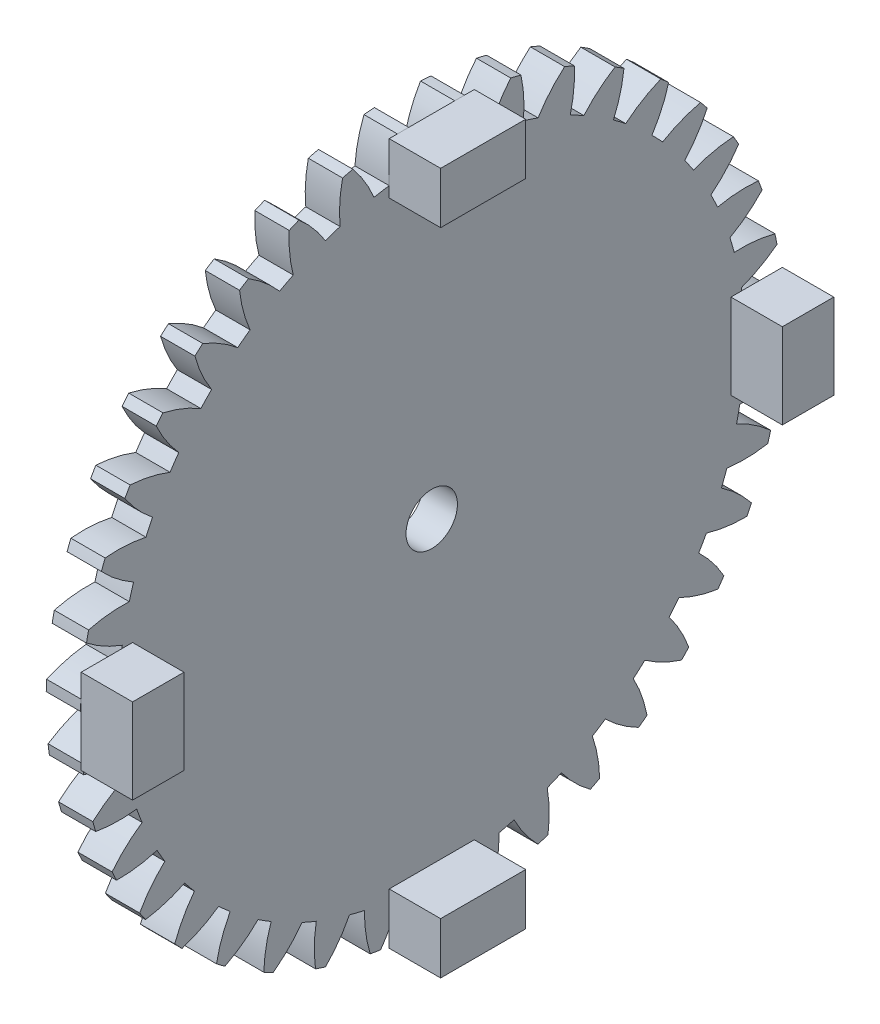
SolidWorks part; units mm, degrees
ref_plane "Plane1" through (0, 0, 0) normal (0, 0, 1) x (1, 0, 0)
ref_plane "Plane2" through (0, 0, 0) normal (0, 1, 0) x (1, 0, 0)
ref_plane "Plane3" through (0, 0, 0) normal (1, 0, 0) x (0, 0, -1)
sketch "HoldingSke" plane through (0, 0, 0) normal (0, 1, 0) x (1, 0, 0)
  line L0 (0, 0) -> (0.7771, -0.6293)
  line L1 (-15, 0) -> (100, 0) construction
  line L2 (0, 0) -> (-2.1039, 2.3779)
  line L3 (0, 0) -> (-11.863, 4.5341)
  line L4 (0, 0) -> (6.7114, 5.4348)
  line L5 (0, 0) -> (-46.8476, -17.4728)
  line L6 (0, 0) -> (-1.6579, -1.1186)
  line L7 (-2.1039, 2.3779) -> (8.6586, 51.2059)
  line L8 (-76.2, 54.61) -> (-75.7, 54.61)
  line L9 (-71.009, 38.7566) -> (-53.1078, 45.2721)
  line L10 (-76.2, 71.12) -> (104.1128, 71.12)
  line L11 (0, 0) -> (-2, 0)
  line L12 (-76.2, 101.6) -> (-76.162, 101.6)
  line L13 (24.9733, 27.94) -> (52.9518, 28.4284)
  line L14 (24.9733, 27.94) -> (24.9743, 27.94)
  line L15 (24.9733, 27.94) -> (100.4006, 29.5858)
  line L16 (-63.627, -1) -> (-12.827, -1)
  circle A0 centre (0, 0) radius 1.5
  circle A1 centre (0, 0) radius 18.249
  circle A2 centre (0, 0) radius 37.5
  circle A3 centre (0, 0) radius 1.5
  dimension "MHD" = 36.498
  dimension "Hub_dia" = 75
  dimension "Bore" = 3
  dimension "MBD" = 3
  dimension "Num_teeth" = 39
  dimension "Pitch" = 1
  dimension "Overall_len" = 50
  dimension "Show_teeth" = 39
  dimension "Thickness" = 2
  dimension "OAL" = 50.0001
  dimension "T_dim" = 0.5
  dimension "Ap" = 20
  dimension "H" = 19.05
  dimension "Pitch_radius" = 180.3128
  dimension "Width" = 2
  dimension "Backlash" = 0.038
  dimension "Addendum_fac" = 1
  dimension "Dedendum_fac" = 1.25
  dimension "Clearance_fac" = 0.25
  dimension "Dedendum_add" = 0.001
  dimension "Module" = 1
sketch "BasProSke" plane through (0, 0, 0) normal (0, 1, 0) x (1, 0, 0)
  line L0 (-10, 0) -> (60, 0) construction
  line L1 (0, 0) -> (0, 20.5)
  line L2 (0, 0) -> (2, 0)
  line L3 (2, 0) -> (2, 20.5)
  line L4 (2, 20.5) -> (0, 20.5)
  dimension "Thickness" = 2
  dimension "Diameter" = 41
revolve "Base-Revolve" add sketch "BasProSke" angle 360 about L0
sketch "TooCutSke" plane through (0, 0, 0) normal (1, 0, 0) x (0, 0, -1)
  line L1 (0, 0) -> (0, 107) construction
  line L2 (0, 0) -> (-0.8517, 19.4814) construction
  line L3 (0, 0) -> (-3.1361, 38.8471) construction
  line L4 (-0.8517, 19.4814) -> (-1.568, 19.4236) construction
  arc A0 (0.4501, 18.2434) -> (-0.4501, 18.2434) centre (0, 0) ccw
  arc A1 (1.358, 20.4804) -> (-1.358, 20.4804) centre (0, 0) ccw
  circle A2 centre (0, 0) radius 19.5 construction
  circle A3 centre (0, 0) radius 18.324 construction
  arc A4 (-0.4501, 18.2434) -> (-1.358, 20.4804) centre (-8.0443, 16.4638) ccw
  arc A5 (1.358, 20.4804) -> (0.4501, 18.2434) centre (8.0443, 16.4638) ccw
  dimension "Root_dia" = 36.498
  dimension "Overcut_dia" = 41.0508
  dimension "Pitch_dia" = 39
  dimension "Base_dia" = 36.648
  dimension "Flank_rad" = 7.8
  dimension "Half_ang" = 4.615
  dimension "Half_CT" = 0.7187
extrude "ToothCut" cut sketch "TooCutSke" along normal through all
fillet "Breaks" [suppressed] radius 0.02
fillet "RootFillets" [suppressed] radius 0.251
pattern_circular "TeethCuts" count 39 every 9.231 about axis through (-10, 0, 0) along (1, 0, 0) of "ToothCut", "RootFillets", "Breaks"
sketch "HubNeaOneSke" plane through (0, 0, 0) normal (-1, 0, 0) x (0, 0, 1)
  circle A0 centre (0, 0) radius 18.249
  dimension "Diameter" = 36.498
extrude "HubNearOne" [suppressed] add sketch "HubNeaOneSke" along normal blind 48.0001
sketch "HubNeaBotSke" plane through (0, 0, 0) normal (-1, 0, 0) x (0, 0, 1)
  circle A0 centre (0, 0) radius 18.249
  dimension "Diameter" = 36.498
extrude "HubNearBoth" [suppressed] add sketch "HubNeaBotSke" along normal blind 24
ref_plane "FarPln" through (2, 0, 0) normal (1, 0, 0) x (0, 0, -1)
sketch "HubFarSke" plane through (2, 0, 0) normal (1, 0, 0) x (0, 0, -1)
  circle A0 centre (0, 0) radius 18.249
  dimension "Diameter" = 36.498
extrude "HubFar" [suppressed] add sketch "HubFarSke" along normal blind 24
sketch "BorSke" plane through (0, 0, 0) normal (1, 0, 0) x (0, 0, -1)
  circle A0 centre (0, 0) radius 1.5
  dimension "Diameter" = 3
extrude "Bore" cut sketch "BorSke" along normal mid plane 100.0001
sketch "KeySke" plane through (0, 0, 0) normal (1, 0, 0) x (0, 0, -1)
  line L0 (-0.6, 0) -> (-0.6, 2)
  line L1 (-0.6, 2) -> (0.6, 2)
  line L2 (0.6, 2) -> (0.6, 0)
  line L3 (0, 0) -> (0, 34) construction
  line L4 (-0.6, 0) -> (0.6, 0)
  dimension "Offset" = 2
  dimension "Width" = 1.2
extrude "Keyway" [suppressed] cut sketch "KeySke" along normal mid plane 100.0001
pattern_circular "Keyway2" [suppressed] count 2 every 90 about axis through (-10, 0, 0) along (1, 0, 0)
sketch "Croquis1" plane through (2, 0, 0) normal (1, 0, 0) x (0, 0, -1)
  line L0 (0, 0) -> (0, 18.249) construction
  line L6 (17.4559, -2.4822) -> (20.4559, -2.4822)
  line L22 (2.4822, 17.4559) -> (-2.4822, 17.4559)
  line L23 (2.4822, 17.4559) -> (2.4822, 20.4559)
  line L24 (2.4822, 20.4559) -> (-2.4822, 20.4559)
  line L25 (-2.4822, 17.4559) -> (-2.4822, 20.4559)
  line L26 (2.4822, 17.4559) -> (-2.4822, 20.4559) construction
  line L27 (2.4822, 20.4559) -> (-2.4822, 17.4559) construction
  line L28 (17.4559, -2.4822) -> (17.4559, 2.4822)
  line L29 (17.4559, 2.4822) -> (20.4559, 2.4822)
  line L30 (20.4559, -2.4822) -> (20.4559, 2.4822)
  line L31 (-2.4822, -17.4559) -> (-2.4822, -20.4559)
  line L32 (-2.4822, -17.4559) -> (2.4822, -17.4559)
  line L33 (2.4822, -17.4559) -> (2.4822, -20.4559)
  line L34 (-2.4822, -20.4559) -> (2.4822, -20.4559)
  line L35 (-17.4559, 2.4822) -> (-20.4559, 2.4822)
  line L36 (-17.4559, 2.4822) -> (-17.4559, -2.4822)
  line L37 (-17.4559, -2.4822) -> (-20.4559, -2.4822)
  line L38 (-20.4559, 2.4822) -> (-20.4559, -2.4822)
  arc A156 (-20.4934, 0.5186) -> (-18.2468, -0.2849) centre (-16.7744, 7.3749) ccw
  arc A157 (-18.2468, -0.2849) -> (-18.2105, -1.1843) centre (0, 0) ccw
  arc A158 (-18.2105, -1.1843) -> (-20.3853, -2.1659) centre (-16.1266, -8.7007) ccw
  arc A159 (-20.3853, -2.1659) -> (-20.3112, -2.7755) centre (0, 0) ccw
  arc A160 (-20.3112, -2.7755) -> (-17.9648, -3.2082) centre (-17.7402, 4.5886) ccw
  arc A161 (-17.9648, -3.2082) -> (-17.7847, -4.0901) centre (0, 0) ccw
  arc A162 (-17.7847, -4.0901) -> (-19.7738, -5.4079) centre (-14.522, -11.175) ccw
  arc A163 (-19.7738, -5.4079) -> (-19.603, -5.9977) centre (0, 0) ccw
  arc A164 (-19.603, -5.9977) -> (-17.2175, -6.0484) centre (-18.2465, 1.6834) ccw
  arc A165 (-17.2175, -6.0484) -> (-16.8983, -6.89) centre (0, 0) ccw
  arc A166 (-16.8983, -6.89) -> (-18.6503, -8.5098) centre (-12.5414, -13.3597) ccw
  arc A167 (-18.6503, -8.5098) -> (-18.387, -9.0646) centre (0, 0) ccw
  arc A168 (-18.387, -9.0646) -> (-16.0243, -8.732) centre (-18.2803, -1.2653) ccw
  arc A169 (-16.0243, -8.732) -> (-15.5743, -9.5115) centre (0, 0) ccw
  arc A170 (-15.5743, -9.5115) -> (-17.0437, -11.3914) centre (-10.2359, -15.1985) ccw
  arc A171 (-17.0437, -11.3914) -> (-16.6949, -11.8967) centre (0, 0) ccw
  arc A172 (-16.6949, -11.8967) -> (-14.4161, -11.1894) centre (-17.8406, -4.1813) ccw
  arc A173 (-14.4161, -11.1894) -> (-13.8468, -11.8866) centre (0, 0) ccw
  arc A174 (-13.8468, -11.8866) -> (-14.9957, -13.9778) centre (-7.6654, -16.6437) ccw
  arc A175 (-14.9957, -13.9778) -> (-14.5703, -14.4207) centre (0, 0) ccw
  arc A176 (-14.5703, -14.4207) -> (-12.4345, -13.357) centre (-16.9388, -6.989) ccw
  arc A177 (-12.4345, -13.357) -> (-11.7608, -13.9539) centre (0, 0) ccw
  arc A178 (-11.7608, -13.9539) -> (-12.5593, -16.2023) centre (-4.8963, -17.6577) ccw
  arc A179 (-12.5593, -16.2023) -> (-12.0684, -16.5712) centre (0, 0) ccw
  arc A180 (-12.0684, -16.5712) -> (-10.1309, -15.1786) centre (-15.5984, -9.6156) ccw
  arc A181 (-10.1309, -15.1786) -> (-9.3701, -15.6597) centre (0, 0) ccw
  arc A182 (-9.3701, -15.6597) -> (-9.7976, -18.0071) centre (-2.0004, -18.2145) ccw
  arc A183 (-9.7976, -18.0071) -> (-9.2539, -18.2925) centre (0, 0) ccw
  arc A184 (-9.2539, -18.2925) -> (-7.5649, -16.6072) centre (-13.8539, -11.9933) ccw
  arc A185 (-7.5649, -16.6072) -> (-6.7368, -16.96) centre (0, 0) ccw
  arc A186 (-6.7368, -16.96) -> (-6.7822, -19.3456) centre (0.9474, -18.2995) ccw
  arc A187 (-6.7822, -19.3456) -> (-6.1997, -19.54) centre (0, 0) ccw
  arc A188 (-6.1997, -19.54) -> (-4.8029, -17.6056) centre (-11.7506, -14.0603) ccw
  arc A189 (-4.8029, -17.6056) -> (-3.929, -17.821) centre (0, 0) ccw
  arc A190 (-3.929, -17.821) -> (-3.5911, -20.183) centre (3.8705, -17.9106) ccw
  arc A191 (-3.5911, -20.183) -> (-2.985, -20.2815) centre (0, 0) ccw
  arc A192 (-2.985, -20.2815) -> (-1.9166, -18.1481) centre (-9.343, -15.7631) ccw
  arc A193 (-1.9166, -18.1481) -> (-1.0194, -18.2205) centre (0, 0) ccw
  arc A194 (-1.0194, -18.2205) -> (-0.307, -20.4977) centre (6.6935, -17.0577) ccw
  arc A195 (-0.307, -20.4977) -> (0.307, -20.4977) centre (0, 0) ccw
  arc A196 (0.307, -20.4977) -> (1.0194, -18.2205) centre (-6.6935, -17.0577) ccw
  arc A197 (1.0194, -18.2205) -> (1.9166, -18.1481) centre (0, 0) ccw
  arc A198 (1.9166, -18.1481) -> (2.985, -20.2815) centre (9.343, -15.7631) ccw
  arc A199 (2.985, -20.2815) -> (3.5911, -20.183) centre (0, 0) ccw
  arc A200 (3.5911, -20.183) -> (3.929, -17.821) centre (-3.8705, -17.9106) ccw
  arc A201 (3.929, -17.821) -> (4.8029, -17.6056) centre (0, 0) ccw
  arc A202 (4.8029, -17.6056) -> (6.1997, -19.54) centre (11.7506, -14.0603) ccw
  arc A203 (6.1997, -19.54) -> (6.7822, -19.3456) centre (0, 0) ccw
  arc A204 (6.7822, -19.3456) -> (6.7368, -16.96) centre (-0.9474, -18.2995) ccw
  arc A205 (6.7368, -16.96) -> (7.5649, -16.6072) centre (0, 0) ccw
  arc A206 (7.5649, -16.6072) -> (9.2539, -18.2925) centre (13.8539, -11.9933) ccw
  arc A207 (9.2539, -18.2925) -> (9.7976, -18.0071) centre (0, 0) ccw
  arc A208 (9.7976, -18.0071) -> (9.3701, -15.6597) centre (2.0004, -18.2145) ccw
  arc A209 (9.3701, -15.6597) -> (10.1309, -15.1786) centre (0, 0) ccw
  arc A210 (10.1309, -15.1786) -> (12.0684, -16.5712) centre (15.5984, -9.6156) ccw
  arc A211 (12.0684, -16.5712) -> (12.5593, -16.2023) centre (0, 0) ccw
  arc A212 (12.5593, -16.2023) -> (11.7608, -13.9539) centre (4.8963, -17.6577) ccw
  arc A213 (11.7608, -13.9539) -> (12.4345, -13.357) centre (0, 0) ccw
  arc A214 (12.4345, -13.357) -> (14.5703, -14.4207) centre (16.9388, -6.989) ccw
  arc A215 (14.5703, -14.4207) -> (14.9957, -13.9778) centre (0, 0) ccw
  arc A216 (14.9957, -13.9778) -> (13.8468, -11.8866) centre (7.6654, -16.6437) ccw
  arc A217 (13.8468, -11.8866) -> (14.4161, -11.1894) centre (0, 0) ccw
  arc A218 (14.4161, -11.1894) -> (16.6949, -11.8967) centre (17.8406, -4.1813) ccw
  arc A219 (16.6949, -11.8967) -> (17.0437, -11.3914) centre (0, 0) ccw
  arc A220 (17.0437, -11.3914) -> (15.5743, -9.5115) centre (10.2359, -15.1985) ccw
  arc A221 (15.5743, -9.5115) -> (16.0243, -8.732) centre (0, 0) ccw
  arc A222 (16.0243, -8.732) -> (18.387, -9.0646) centre (18.2803, -1.2653) ccw
  arc A223 (18.387, -9.0646) -> (18.6503, -8.5098) centre (0, 0) ccw
  arc A224 (18.6503, -8.5098) -> (16.8983, -6.89) centre (12.5414, -13.3597) ccw
  arc A225 (16.8983, -6.89) -> (17.2175, -6.0484) centre (0, 0) ccw
  arc A226 (17.2175, -6.0484) -> (19.603, -5.9977) centre (18.2465, 1.6834) ccw
  arc A227 (19.603, -5.9977) -> (19.7738, -5.4079) centre (0, 0) ccw
  arc A228 (19.7738, -5.4079) -> (17.7847, -4.0901) centre (14.522, -11.175) ccw
  arc A229 (17.7847, -4.0901) -> (17.9648, -3.2082) centre (0, 0) ccw
  arc A230 (17.9648, -3.2082) -> (20.3112, -2.7755) centre (17.7402, 4.5886) ccw
  arc A231 (20.3112, -2.7755) -> (20.3853, -2.1659) centre (0, 0) ccw
  arc A232 (20.3853, -2.1659) -> (18.2105, -1.1843) centre (16.1266, -8.7007) ccw
  arc A233 (18.2105, -1.1843) -> (18.2468, -0.2849) centre (0, 0) ccw
  arc A234 (18.2468, -0.2849) -> (20.4934, 0.5186) centre (16.7744, 7.3749) ccw
  arc A235 (20.4934, 0.5186) -> (20.4687, 1.1321) centre (0, 0) ccw
  arc A236 (20.4687, 1.1321) -> (18.1647, 1.7522) centre (17.3134, -6.0012) ccw
  arc A237 (18.1647, 1.7522) -> (18.0562, 2.6458) centre (0, 0) ccw
  arc A238 (18.0562, 2.6458) -> (20.1449, 3.7993) centre (15.3742, 9.9702) ccw
  arc A239 (20.1449, 3.7993) -> (20.022, 4.4009) centre (0, 0) ccw
  arc A240 (20.022, 4.4009) -> (17.6484, 4.6434) centre (18.0519, -3.1462) ccw
  arc A241 (17.6484, 4.6434) -> (17.3979, 5.5079) centre (0, 0) ccw
  arc A242 (17.3979, 5.5079) -> (19.2746, 6.9815) centre (13.5757, 12.3073) ccw
  arc A243 (19.2746, 6.9815) -> (19.0568, 7.5557) centre (0, 0) ccw
  arc A244 (19.0568, 7.5557) -> (16.675, 7.4142) centre (18.3228, -0.2097) ccw
  arc A245 (16.675, 7.4142) -> (16.2891, 8.2274) centre (0, 0) ccw
  arc A246 (16.2891, 8.2274) -> (17.905, 9.983) centre (11.4257, 14.3256) ccw
  arc A247 (17.905, 9.983) -> (17.598, 10.5147) centre (0, 0) ccw
  arc A248 (17.598, 10.5147) -> (15.2697, 9.9931) centre (18.1192, 2.7322) ccw
  arc A249 (15.2697, 9.9931) -> (14.7584, 10.7339) centre (0, 0) ccw
  arc A250 (14.7584, 10.7339) -> (16.0718, 12.7259) centre (8.9798, 15.9729) ccw
  arc A251 (16.0718, 12.7259) -> (15.6834, 13.2015) centre (0, 0) ccw
  arc A252 (15.6834, 13.2015) -> (13.469, 12.3131) centre (17.4463, 5.6033) ccw
  arc A253 (13.469, 12.3131) -> (12.8455, 12.9623) centre (0, 0) ccw
  arc A254 (12.8455, 12.9623) -> (13.8223, 15.1392) centre (6.3013, 17.2065) ccw
  arc A255 (13.8223, 15.1392) -> (13.3627, 15.5463) centre (0, 0) ccw
  arc A256 (13.3627, 15.5463) -> (11.3194, 14.3142) centre (16.3215, 8.3293) ccw
  arc A257 (11.3194, 14.3142) -> (10.5998, 14.855) centre (0, 0) ccw
  arc A258 (10.5998, 14.855) -> (11.2148, 17.1604) centre (3.4595, 17.9945) ccw
  arc A259 (11.2148, 17.1604) -> (10.6958, 17.4885) centre (0, 0) ccw
  arc A260 (10.6958, 17.4885) -> (8.8767, 15.9446) centre (14.774, 10.8396) ccw
  arc A261 (8.8767, 15.9446) -> (8.0796, 16.3629) centre (0, 0) ccw
  arc A262 (8.0796, 16.3629) -> (8.3169, 18.7371) centre (0.5282, 18.3164) ccw
  arc A263 (8.3169, 18.7371) -> (7.752, 18.9778) centre (0, 0) ccw
  arc A264 (7.752, 18.9778) -> (6.204, 17.1621) centre (12.8439, 13.0692) ccw
  arc A265 (6.204, 17.1621) -> (5.3502, 17.4471) centre (0, 0) ccw
  arc A266 (5.3502, 17.4471) -> (5.2035, 19.8286) centre (-2.4168, 18.1639) ccw
  arc A267 (5.2035, 19.8286) -> (4.6073, 19.9755) centre (0, 0) ccw
  arc A268 (4.6073, 19.9755) -> (3.3707, 17.935) centre (10.5811, 14.9602) ccw
  arc A269 (3.3707, 17.935) -> (2.4822, 18.0794) centre (0, 0) ccw
  arc A270 (2.4822, 18.0794) -> (1.9554, 20.4065) centre (-5.2992, 17.541) ccw
  arc A271 (1.9554, 20.4065) -> (1.3434, 20.4559) centre (0, 0) ccw
  arc A272 (1.3434, 20.4559) -> (0.4501, 18.2434) centre (8.0443, 16.4638) ccw
  arc A273 (0.4501, 18.2434) -> (-0.4501, 18.2434) centre (0, 0) ccw
  arc A274 (-0.4501, 18.2434) -> (-1.3434, 20.4559) centre (-8.0443, 16.4638) ccw
  arc A275 (-1.3434, 20.4559) -> (-1.9554, 20.4065) centre (0, 0) ccw
  arc A276 (-1.9554, 20.4065) -> (-2.4822, 18.0794) centre (5.2992, 17.541) ccw
  arc A277 (-2.4822, 18.0794) -> (-3.3707, 17.935) centre (0, 0) ccw
  arc A278 (-3.3707, 17.935) -> (-4.6073, 19.9755) centre (-10.5811, 14.9602) ccw
  arc A279 (-4.6073, 19.9755) -> (-5.2035, 19.8286) centre (0, 0) ccw
  arc A280 (-5.2035, 19.8286) -> (-5.3502, 17.4471) centre (2.4168, 18.1639) ccw
  arc A281 (-5.3502, 17.4471) -> (-6.204, 17.1621) centre (0, 0) ccw
  arc A282 (-6.204, 17.1621) -> (-7.752, 18.9778) centre (-12.8439, 13.0692) ccw
  arc A283 (-7.752, 18.9778) -> (-8.3169, 18.7371) centre (0, 0) ccw
  arc A284 (-8.3169, 18.7371) -> (-8.0796, 16.3629) centre (-0.5282, 18.3164) ccw
  arc A285 (-8.0796, 16.3629) -> (-8.8767, 15.9446) centre (0, 0) ccw
  arc A286 (-8.8767, 15.9446) -> (-10.6958, 17.4885) centre (-14.774, 10.8396) ccw
  arc A287 (-10.6958, 17.4885) -> (-11.2148, 17.1604) centre (0, 0) ccw
  arc A288 (-11.2148, 17.1604) -> (-10.5998, 14.855) centre (-3.4595, 17.9945) ccw
  arc A289 (-10.5998, 14.855) -> (-11.3194, 14.3142) centre (0, 0) ccw
  arc A290 (-11.3194, 14.3142) -> (-13.3627, 15.5463) centre (-16.3215, 8.3293) ccw
  arc A291 (-13.3627, 15.5463) -> (-13.8223, 15.1392) centre (0, 0) ccw
  arc A292 (-13.8223, 15.1392) -> (-12.8455, 12.9623) centre (-6.3013, 17.2065) ccw
  arc A293 (-12.8455, 12.9623) -> (-13.469, 12.3131) centre (0, 0) ccw
  arc A294 (-13.469, 12.3131) -> (-15.6834, 13.2015) centre (-17.4463, 5.6033) ccw
  arc A295 (-15.6834, 13.2015) -> (-16.0718, 12.7259) centre (0, 0) ccw
  arc A296 (-16.0718, 12.7259) -> (-14.7584, 10.7339) centre (-8.9798, 15.9729) ccw
  arc A297 (-14.7584, 10.7339) -> (-15.2697, 9.9931) centre (0, 0) ccw
  arc A298 (-15.2697, 9.9931) -> (-17.598, 10.5147) centre (-18.1192, 2.7322) ccw
  arc A299 (-17.598, 10.5147) -> (-17.905, 9.983) centre (0, 0) ccw
  arc A300 (-17.905, 9.983) -> (-16.2891, 8.2274) centre (-11.4257, 14.3256) ccw
  arc A301 (-16.2891, 8.2274) -> (-16.675, 7.4142) centre (0, 0) ccw
  arc A302 (-16.675, 7.4142) -> (-19.0568, 7.5557) centre (-18.3228, -0.2097) ccw
  arc A303 (-19.0568, 7.5557) -> (-19.2746, 6.9815) centre (0, 0) ccw
  arc A304 (-19.2746, 6.9815) -> (-17.3979, 5.5079) centre (-13.5757, 12.3073) ccw
  arc A305 (-17.3979, 5.5079) -> (-17.6484, 4.6434) centre (0, 0) ccw
  arc A306 (-17.6484, 4.6434) -> (-20.022, 4.4009) centre (-18.0519, -3.1462) ccw
  arc A307 (-20.022, 4.4009) -> (-20.1449, 3.7993) centre (0, 0) ccw
  arc A308 (-20.1449, 3.7993) -> (-18.0562, 2.6458) centre (-15.3742, 9.9702) ccw
  arc A309 (-18.0562, 2.6458) -> (-18.1647, 1.7522) centre (0, 0) ccw
  arc A310 (-18.1647, 1.7522) -> (-20.4687, 1.1321) centre (-17.3134, -6.0012) ccw
  arc A311 (-20.4687, 1.1321) -> (-20.4934, 0.5186) centre (0, 0) ccw
  arc A312 (-20.4934, 0.5186) -> (-18.2468, -0.2849) centre (-16.7744, 7.3749) ccw construction
  arc A313 (-18.2468, -0.2849) -> (-18.2105, -1.1843) centre (0, 0) ccw construction
  arc A314 (-18.2105, -1.1843) -> (-20.3853, -2.1659) centre (-16.1266, -8.7007) ccw construction
  arc A315 (-20.3853, -2.1659) -> (-20.3112, -2.7755) centre (0, 0) ccw construction
  arc A316 (-20.3112, -2.7755) -> (-17.9648, -3.2082) centre (-17.7402, 4.5886) ccw construction
  arc A317 (-17.9648, -3.2082) -> (-17.7847, -4.0901) centre (0, 0) ccw construction
  arc A318 (-17.7847, -4.0901) -> (-19.7738, -5.4079) centre (-14.522, -11.175) ccw construction
  arc A319 (-19.7738, -5.4079) -> (-19.603, -5.9977) centre (0, 0) ccw construction
  arc A320 (-19.603, -5.9977) -> (-17.2175, -6.0484) centre (-18.2465, 1.6834) ccw construction
  arc A321 (-17.2175, -6.0484) -> (-16.8983, -6.89) centre (0, 0) ccw construction
  arc A322 (-16.8983, -6.89) -> (-18.6503, -8.5098) centre (-12.5414, -13.3597) ccw construction
  arc A323 (-18.6503, -8.5098) -> (-18.387, -9.0646) centre (0, 0) ccw construction
  arc A324 (-18.387, -9.0646) -> (-16.0243, -8.732) centre (-18.2803, -1.2653) ccw construction
  arc A325 (-16.0243, -8.732) -> (-15.5743, -9.5115) centre (0, 0) ccw construction
  arc A326 (-15.5743, -9.5115) -> (-17.0437, -11.3914) centre (-10.2359, -15.1985) ccw construction
  arc A327 (-17.0437, -11.3914) -> (-16.6949, -11.8967) centre (0, 0) ccw construction
  arc A328 (-16.6949, -11.8967) -> (-14.4161, -11.1894) centre (-17.8406, -4.1813) ccw construction
  arc A329 (-14.4161, -11.1894) -> (-13.8468, -11.8866) centre (0, 0) ccw construction
  arc A330 (-13.8468, -11.8866) -> (-14.9957, -13.9778) centre (-7.6654, -16.6437) ccw construction
  arc A331 (-14.9957, -13.9778) -> (-14.5703, -14.4207) centre (0, 0) ccw construction
  arc A332 (-14.5703, -14.4207) -> (-12.4345, -13.357) centre (-16.9388, -6.989) ccw construction
  arc A333 (-12.4345, -13.357) -> (-11.7608, -13.9539) centre (0, 0) ccw construction
  arc A334 (-11.7608, -13.9539) -> (-12.5593, -16.2023) centre (-4.8963, -17.6577) ccw construction
  arc A335 (-12.5593, -16.2023) -> (-12.0684, -16.5712) centre (0, 0) ccw construction
  arc A336 (-12.0684, -16.5712) -> (-10.1309, -15.1786) centre (-15.5984, -9.6156) ccw construction
  arc A337 (-10.1309, -15.1786) -> (-9.3701, -15.6597) centre (0, 0) ccw construction
  arc A338 (-9.3701, -15.6597) -> (-9.7976, -18.0071) centre (-2.0004, -18.2145) ccw construction
  arc A339 (-9.7976, -18.0071) -> (-9.2539, -18.2925) centre (0, 0) ccw construction
  arc A340 (-9.2539, -18.2925) -> (-7.5649, -16.6072) centre (-13.8539, -11.9933) ccw construction
  arc A341 (-7.5649, -16.6072) -> (-6.7368, -16.96) centre (0, 0) ccw construction
  arc A342 (-6.7368, -16.96) -> (-6.7822, -19.3456) centre (0.9474, -18.2995) ccw construction
  arc A343 (-6.7822, -19.3456) -> (-6.1997, -19.54) centre (0, 0) ccw construction
  arc A344 (-6.1997, -19.54) -> (-4.8029, -17.6056) centre (-11.7506, -14.0603) ccw construction
  arc A345 (-4.8029, -17.6056) -> (-3.929, -17.821) centre (0, 0) ccw construction
  arc A346 (-3.929, -17.821) -> (-3.5911, -20.183) centre (3.8705, -17.9106) ccw construction
  arc A347 (-3.5911, -20.183) -> (-2.985, -20.2815) centre (0, 0) ccw construction
  arc A348 (-2.985, -20.2815) -> (-1.9166, -18.1481) centre (-9.343, -15.7631) ccw construction
  arc A349 (-1.9166, -18.1481) -> (-1.0194, -18.2205) centre (0, 0) ccw construction
  arc A350 (-1.0194, -18.2205) -> (-0.307, -20.4977) centre (6.6935, -17.0577) ccw construction
  arc A351 (-0.307, -20.4977) -> (0.307, -20.4977) centre (0, 0) ccw construction
  arc A352 (0.307, -20.4977) -> (1.0194, -18.2205) centre (-6.6935, -17.0577) ccw construction
  arc A353 (1.0194, -18.2205) -> (1.9166, -18.1481) centre (0, 0) ccw construction
  arc A354 (1.9166, -18.1481) -> (2.985, -20.2815) centre (9.343, -15.7631) ccw construction
  arc A355 (2.985, -20.2815) -> (3.5911, -20.183) centre (0, 0) ccw construction
  arc A356 (3.5911, -20.183) -> (3.929, -17.821) centre (-3.8705, -17.9106) ccw construction
  arc A357 (3.929, -17.821) -> (4.8029, -17.6056) centre (0, 0) ccw construction
  arc A358 (4.8029, -17.6056) -> (6.1997, -19.54) centre (11.7506, -14.0603) ccw construction
  arc A359 (6.1997, -19.54) -> (6.7822, -19.3456) centre (0, 0) ccw construction
  arc A360 (6.7822, -19.3456) -> (6.7368, -16.96) centre (-0.9474, -18.2995) ccw construction
  arc A361 (6.7368, -16.96) -> (7.5649, -16.6072) centre (0, 0) ccw construction
  arc A362 (7.5649, -16.6072) -> (9.2539, -18.2925) centre (13.8539, -11.9933) ccw construction
  arc A363 (9.2539, -18.2925) -> (9.7976, -18.0071) centre (0, 0) ccw construction
  arc A364 (9.7976, -18.0071) -> (9.3701, -15.6597) centre (2.0004, -18.2145) ccw construction
  arc A365 (9.3701, -15.6597) -> (10.1309, -15.1786) centre (0, 0) ccw construction
  arc A366 (10.1309, -15.1786) -> (12.0684, -16.5712) centre (15.5984, -9.6156) ccw construction
  arc A367 (12.0684, -16.5712) -> (12.5593, -16.2023) centre (0, 0) ccw construction
  arc A368 (12.5593, -16.2023) -> (11.7608, -13.9539) centre (4.8963, -17.6577) ccw construction
  arc A369 (11.7608, -13.9539) -> (12.4345, -13.357) centre (0, 0) ccw construction
  arc A370 (12.4345, -13.357) -> (14.5703, -14.4207) centre (16.9388, -6.989) ccw construction
  arc A371 (14.5703, -14.4207) -> (14.9957, -13.9778) centre (0, 0) ccw construction
  arc A372 (14.9957, -13.9778) -> (13.8468, -11.8866) centre (7.6654, -16.6437) ccw construction
  arc A373 (13.8468, -11.8866) -> (14.4161, -11.1894) centre (0, 0) ccw construction
  arc A374 (14.4161, -11.1894) -> (16.6949, -11.8967) centre (17.8406, -4.1813) ccw construction
  arc A375 (16.6949, -11.8967) -> (17.0437, -11.3914) centre (0, 0) ccw construction
  arc A376 (17.0437, -11.3914) -> (15.5743, -9.5115) centre (10.2359, -15.1985) ccw construction
  arc A377 (15.5743, -9.5115) -> (16.0243, -8.732) centre (0, 0) ccw construction
  arc A378 (16.0243, -8.732) -> (18.387, -9.0646) centre (18.2803, -1.2653) ccw construction
  arc A379 (18.387, -9.0646) -> (18.6503, -8.5098) centre (0, 0) ccw construction
  arc A380 (18.6503, -8.5098) -> (16.8983, -6.89) centre (12.5414, -13.3597) ccw construction
  arc A381 (16.8983, -6.89) -> (17.2175, -6.0484) centre (0, 0) ccw construction
  arc A382 (17.2175, -6.0484) -> (19.603, -5.9977) centre (18.2465, 1.6834) ccw construction
  arc A383 (19.603, -5.9977) -> (19.7738, -5.4079) centre (0, 0) ccw construction
  arc A384 (19.7738, -5.4079) -> (17.7847, -4.0901) centre (14.522, -11.175) ccw construction
  arc A385 (17.7847, -4.0901) -> (17.9648, -3.2082) centre (0, 0) ccw construction
  arc A386 (17.9648, -3.2082) -> (20.3112, -2.7755) centre (17.7402, 4.5886) ccw construction
  arc A387 (20.3112, -2.7755) -> (20.3853, -2.1659) centre (0, 0) ccw construction
  arc A388 (20.3853, -2.1659) -> (18.2105, -1.1843) centre (16.1266, -8.7007) ccw construction
  arc A389 (18.2105, -1.1843) -> (18.2468, -0.2849) centre (0, 0) ccw construction
  arc A390 (18.2468, -0.2849) -> (20.4934, 0.5186) centre (16.7744, 7.3749) ccw construction
  arc A391 (20.4934, 0.5186) -> (20.4687, 1.1321) centre (0, 0) ccw construction
  arc A392 (20.4687, 1.1321) -> (18.1647, 1.7522) centre (17.3134, -6.0012) ccw construction
  arc A393 (18.1647, 1.7522) -> (18.0562, 2.6458) centre (0, 0) ccw construction
  arc A394 (18.0562, 2.6458) -> (20.1449, 3.7993) centre (15.3742, 9.9702) ccw construction
  arc A395 (20.1449, 3.7993) -> (20.022, 4.4009) centre (0, 0) ccw construction
  arc A396 (20.022, 4.4009) -> (17.6484, 4.6434) centre (18.0519, -3.1462) ccw construction
  arc A397 (17.6484, 4.6434) -> (17.3979, 5.5079) centre (0, 0) ccw construction
  arc A398 (17.3979, 5.5079) -> (19.2746, 6.9815) centre (13.5757, 12.3073) ccw construction
  arc A399 (19.2746, 6.9815) -> (19.0568, 7.5557) centre (0, 0) ccw construction
  arc A400 (19.0568, 7.5557) -> (16.675, 7.4142) centre (18.3228, -0.2097) ccw construction
  arc A401 (16.675, 7.4142) -> (16.2891, 8.2274) centre (0, 0) ccw construction
  arc A402 (16.2891, 8.2274) -> (17.905, 9.983) centre (11.4257, 14.3256) ccw construction
  arc A403 (17.905, 9.983) -> (17.598, 10.5147) centre (0, 0) ccw construction
  arc A404 (17.598, 10.5147) -> (15.2697, 9.9931) centre (18.1192, 2.7322) ccw construction
  arc A405 (15.2697, 9.9931) -> (14.7584, 10.7339) centre (0, 0) ccw construction
  arc A406 (14.7584, 10.7339) -> (16.0718, 12.7259) centre (8.9798, 15.9729) ccw construction
  arc A407 (16.0718, 12.7259) -> (15.6834, 13.2015) centre (0, 0) ccw construction
  arc A408 (15.6834, 13.2015) -> (13.469, 12.3131) centre (17.4463, 5.6033) ccw construction
  arc A409 (13.469, 12.3131) -> (12.8455, 12.9623) centre (0, 0) ccw construction
  arc A410 (12.8455, 12.9623) -> (13.8223, 15.1392) centre (6.3013, 17.2065) ccw construction
  arc A411 (13.8223, 15.1392) -> (13.3627, 15.5463) centre (0, 0) ccw construction
  arc A412 (13.3627, 15.5463) -> (11.3194, 14.3142) centre (16.3215, 8.3293) ccw construction
  arc A413 (11.3194, 14.3142) -> (10.5998, 14.855) centre (0, 0) ccw construction
  arc A414 (10.5998, 14.855) -> (11.2148, 17.1604) centre (3.4595, 17.9945) ccw construction
  arc A415 (11.2148, 17.1604) -> (10.6958, 17.4885) centre (0, 0) ccw construction
  arc A416 (10.6958, 17.4885) -> (8.8767, 15.9446) centre (14.774, 10.8396) ccw construction
  arc A417 (8.8767, 15.9446) -> (8.0796, 16.3629) centre (0, 0) ccw construction
  arc A418 (8.0796, 16.3629) -> (8.3169, 18.7371) centre (0.5282, 18.3164) ccw construction
  arc A419 (8.3169, 18.7371) -> (7.752, 18.9778) centre (0, 0) ccw construction
  arc A420 (7.752, 18.9778) -> (6.204, 17.1621) centre (12.8439, 13.0692) ccw construction
  arc A421 (6.204, 17.1621) -> (5.3502, 17.4471) centre (0, 0) ccw construction
  arc A422 (5.3502, 17.4471) -> (5.2035, 19.8286) centre (-2.4168, 18.1639) ccw construction
  arc A423 (5.2035, 19.8286) -> (4.6073, 19.9755) centre (0, 0) ccw construction
  arc A424 (4.6073, 19.9755) -> (3.3707, 17.935) centre (10.5811, 14.9602) ccw construction
  arc A425 (3.3707, 17.935) -> (2.4822, 18.0794) centre (0, 0) ccw construction
  arc A426 (2.4822, 18.0794) -> (1.9554, 20.4065) centre (-5.2992, 17.541) ccw construction
  arc A427 (1.9554, 20.4065) -> (1.3434, 20.4559) centre (0, 0) ccw construction
  arc A428 (1.3434, 20.4559) -> (0.4501, 18.2434) centre (8.0443, 16.4638) ccw construction
  arc A429 (0.4501, 18.2434) -> (-0.4501, 18.2434) centre (0, 0) ccw construction
  arc A430 (-0.4501, 18.2434) -> (-1.3434, 20.4559) centre (-8.0443, 16.4638) ccw construction
  arc A431 (-1.3434, 20.4559) -> (-1.9554, 20.4065) centre (0, 0) ccw construction
  arc A432 (-1.9554, 20.4065) -> (-2.4822, 18.0794) centre (5.2992, 17.541) ccw construction
  arc A433 (-2.4822, 18.0794) -> (-3.3707, 17.935) centre (0, 0) ccw construction
  arc A434 (-3.3707, 17.935) -> (-4.6073, 19.9755) centre (-10.5811, 14.9602) ccw construction
  arc A435 (-4.6073, 19.9755) -> (-5.2035, 19.8286) centre (0, 0) ccw construction
  arc A436 (-5.2035, 19.8286) -> (-5.3502, 17.4471) centre (2.4168, 18.1639) ccw construction
  arc A437 (-5.3502, 17.4471) -> (-6.204, 17.1621) centre (0, 0) ccw construction
  arc A438 (-6.204, 17.1621) -> (-7.752, 18.9778) centre (-12.8439, 13.0692) ccw construction
  arc A439 (-7.752, 18.9778) -> (-8.3169, 18.7371) centre (0, 0) ccw construction
  arc A440 (-8.3169, 18.7371) -> (-8.0796, 16.3629) centre (-0.5282, 18.3164) ccw construction
  arc A441 (-8.0796, 16.3629) -> (-8.8767, 15.9446) centre (0, 0) ccw construction
  arc A442 (-8.8767, 15.9446) -> (-10.6958, 17.4885) centre (-14.774, 10.8396) ccw construction
  arc A443 (-10.6958, 17.4885) -> (-11.2148, 17.1604) centre (0, 0) ccw construction
  arc A444 (-11.2148, 17.1604) -> (-10.5998, 14.855) centre (-3.4595, 17.9945) ccw construction
  arc A445 (-10.5998, 14.855) -> (-11.3194, 14.3142) centre (0, 0) ccw construction
  arc A446 (-11.3194, 14.3142) -> (-13.3627, 15.5463) centre (-16.3215, 8.3293) ccw construction
  arc A447 (-13.3627, 15.5463) -> (-13.8223, 15.1392) centre (0, 0) ccw construction
  arc A448 (-13.8223, 15.1392) -> (-12.8455, 12.9623) centre (-6.3013, 17.2065) ccw construction
  arc A449 (-12.8455, 12.9623) -> (-13.469, 12.3131) centre (0, 0) ccw construction
  arc A450 (-13.469, 12.3131) -> (-15.6834, 13.2015) centre (-17.4463, 5.6033) ccw construction
  arc A451 (-15.6834, 13.2015) -> (-16.0718, 12.7259) centre (0, 0) ccw construction
  arc A452 (-16.0718, 12.7259) -> (-14.7584, 10.7339) centre (-8.9798, 15.9729) ccw construction
  arc A453 (-14.7584, 10.7339) -> (-15.2697, 9.9931) centre (0, 0) ccw construction
  arc A454 (-15.2697, 9.9931) -> (-17.598, 10.5147) centre (-18.1192, 2.7322) ccw construction
  arc A455 (-17.598, 10.5147) -> (-17.905, 9.983) centre (0, 0) ccw construction
  arc A456 (-17.905, 9.983) -> (-16.2891, 8.2274) centre (-11.4257, 14.3256) ccw construction
  arc A457 (-16.2891, 8.2274) -> (-16.675, 7.4142) centre (0, 0) ccw construction
  arc A458 (-16.675, 7.4142) -> (-19.0568, 7.5557) centre (-18.3228, -0.2097) ccw construction
  arc A459 (-19.0568, 7.5557) -> (-19.2746, 6.9815) centre (0, 0) ccw construction
  arc A460 (-19.2746, 6.9815) -> (-17.3979, 5.5079) centre (-13.5757, 12.3073) ccw construction
  arc A461 (-17.3979, 5.5079) -> (-17.6484, 4.6434) centre (0, 0) ccw construction
  arc A462 (-17.6484, 4.6434) -> (-20.022, 4.4009) centre (-18.0519, -3.1462) ccw construction
  arc A463 (-20.022, 4.4009) -> (-20.1449, 3.7993) centre (0, 0) ccw construction
  arc A464 (-20.1449, 3.7993) -> (-18.0562, 2.6458) centre (-15.3742, 9.9702) ccw construction
  arc A465 (-18.0562, 2.6458) -> (-18.1647, 1.7522) centre (0, 0) ccw construction
  arc A466 (-18.1647, 1.7522) -> (-20.4687, 1.1321) centre (-17.3134, -6.0012) ccw construction
  arc A467 (-20.4687, 1.1321) -> (-20.4934, 0.5186) centre (0, 0) ccw construction
  point P3 (0, 18.9559)
  point P11 (-20.1449, 0.5186)
  point P18 (0, 0)
  point P24 (-20.4559, -2.7755)
  point P63 (0, 0)
  dimension "D2" = 3
  dimension "D3" = 4
  dimension "D1" = 0
extrude "Saliente-Extruir1" add sketch "Croquis1" along normal blind 3
equation "' \"Module@HoldingSke\" = 6.35"
equation "' \"Num_teeth@HoldingSke\" = 12"
equation "' \"Ap@HoldingSke\" =  20"
equation "' \"Ap@HoldingSke\" = 20"
equation "' \"Width@HoldingSke\" = 0.5 * 25.4"
equation "' \"Hub_dia@HoldingSke\"= 1 * 25.4"
equation "' \"Hub_dia@HoldingSke\" = 1 * 25.4"
equation "' \"Overall_len@HoldingSke\" = 1.0 * 25.4"
equation "' \"Bore@HoldingSke\" = 0.75 * 25.4"
equation "' \"T_dim@HoldingSke\" = 0.1 * 25.4"
equation "' \"Width@KeySke\" = 0.25 * 25.4"
equation "' \"Show_teeth@HoldingSke\" = 13"
equation "' \"Backlash@HoldingSke\" = 0.009 * 25.4"
equation "' \"Addendum_fac@HoldingSke\" = 1.0"
equation "' \"Dedendum_fac@HoldingSke\" = 1.25"
equation "' \"Dedendum_add@HoldingSke\" = 0.00005 * 25.4"
equation "' \"Clearance_fac@HoldingSke\" = 0.25"
equation "\"Pitch@HoldingSke\" = 1 / \"Module@HoldingSke\""
equation "\"Overcut_dia@TooCutSke\" = (\"Num_teeth@HoldingSke\" + 2 * \"Addendum_fac@HoldingSke\") / \"Pitch@HoldingSke\" + 0.002 * 25.4"
equation "\"Pitch_dia@TooCutSke\" = \"Num_teeth@HoldingSke\" / \"Pitch@HoldingSke\""
equation "\"Base_dia@TooCutSke\" = \"Num_teeth@HoldingSke\" / \"Pitch@HoldingSke\" * cos((\"Ap@HoldingSke\"  * 3.14159265 / 180))"
equation "\"Root_dia@TooCutSke\" = (\"Num_teeth@HoldingSke\" + 2) / \"Pitch@HoldingSke\" - 2 * (\"Addendum_fac@HoldingSke\" + \"Dedendum_fac@HoldingSke\") / \"Pitch@HoldingSke\" - \"Dedendum_add@HoldingSke\" * 2"
equation "\"Half_ang@TooCutSke\" = 180 / \"Num_teeth@HoldingSke\""
equation "\"Half_CT@TooCutSke\" = \"Num_teeth@HoldingSke\" / \"Pitch@HoldingSke\" * sin((3.14159265 / 2 / \"Num_teeth@HoldingSke\")) / 2 - 7 * \"Backlash@HoldingSke\" / 4"
equation "\"Flank_rad@TooCutSke\" = \"Num_teeth@HoldingSke\" / \"Pitch@HoldingSke\" / 5"
equation "\"Radius@RootFillets\" = \"Clearance_fac@HoldingSke\" / \"Pitch@HoldingSke\" + \"Dedendum_add@HoldingSke\""
equation "\"Break_rad@Breaks\" = 0.02 / \"Pitch@HoldingSke\""
equation "\"Thickness@HoldingSke\" = \"Width@HoldingSke\""
equation "\"OAL@HoldingSke\" = \"Thickness@HoldingSke\""
equation "\"MHD@HoldingSke\" = (\"Num_teeth@HoldingSke\" + 2) / \"Pitch@HoldingSke\" - 2 * (\"Addendum_fac@HoldingSke\" + \"Dedendum_fac@HoldingSke\")  / \"Pitch@HoldingSke\" - \"Dedendum_add@HoldingSke\" * 2"
equation "\"MBD@HoldingSke\" = (\"Num_teeth@HoldingSke\" + 2) / \"Pitch@HoldingSke\" - 2 * (\"Addendum_fac@HoldingSke\" + \"Dedendum_fac@HoldingSke\")  / \"Pitch@HoldingSke\" - \"Dedendum_add@HoldingSke\" * 2 - 0.002 * 25.4"
equation "\"MHD@HoldingSke\" = ((sgn( \"MHD@HoldingSke\" - \"Hub_dia@HoldingSke\" )-1)*( \"MHD@HoldingSke\" - \"Hub_dia@HoldingSke\" ))/-2+ \"Hub_dia@HoldingSke\""
equation "\"MBD@HoldingSke\" = ((sgn( \"MBD@HoldingSke\" - \"Bore@HoldingSke\" )-1)*( \"MBD@HoldingSke\" - \"Bore@HoldingSke\" ))/-2+ \"Bore@HoldingSke\""
equation "\"OAL@HoldingSke\" = ((sgn( \"OAL@HoldingSke\" - \"Overall_len@HoldingSke\" )+1)*( \"OAL@HoldingSke\" - \"Overall_len@HoldingSke\" ))/2 + \"Overall_len@HoldingSke\" + 0.000002 * 25.4"
equation "\"Num_teeth@TeethCuts\" = int( \"Show_teeth@HoldingSke\" ) + 1"
equation "\"Num_teeth@TeethCuts\" = ((sgn( \"Num_teeth@TeethCuts\" - \"Num_teeth@HoldingSke\" )-1)*( \"Num_teeth@TeethCuts\" - \"Num_teeth@HoldingSke\" ))/-2+ \"Num_teeth@HoldingSke\""
equation "\"Num_teeth@TeethCuts\" = ((sgn( \"Num_teeth@TeethCuts\" - 2.0)+1)*( \"Num_teeth@TeethCuts\" - 2.0))/2 +2.0"
equation "\"Angle@TeethCuts\" = 360.0 / \"Num_teeth@HoldingSke\""
equation "\"Diameter@BasProSke\" = (\"Num_teeth@HoldingSke\" + 2 * \"Addendum_fac@HoldingSke\") / \"Pitch@HoldingSke\""
equation "\"Thickness@BasProSke\"  = \"Thickness@HoldingSke\""
equation "' \"Fillet_rad@BasProSke\" =  \"Thickness@HoldingSke\" * 0.05"
equation "' \"Fillet_rad@BasProSke\" = \"Thickness@HoldingSke\" * 0.05"
equation "\"MHD@HoldingSke\" = ((sgn( \"MHD@HoldingSke\" - \"Root_dia@TooCutSke\" )-1)*( \"MHD@HoldingSke\" - \"Root_dia@TooCutSke\" ))/-2+ \"Root_dia@TooCutSke\""
equation "\"Diameter@HubNeaOneSke\" = \"MHD@HoldingSke\""
equation "\"Length@HubNearOne\" = \"OAL@HoldingSke\" - \"Thickness@BasProSke\""
equation "\"Diameter@HubNeaBotSke\" = \"MHD@HoldingSke\""
equation "\"Length@HubNearBoth\" = ( \"OAL@HoldingSke\" - \"Thickness@BasProSke\" ) / 2.0"
equation "\"Thickness@FarPln\" = \"Thickness@BasProSke\""
equation "\"Diameter@HubFarSke\" = \"MHD@HoldingSke\""
equation "\"Length@HubFar\" = ( \"OAL@HoldingSke\" - \"Thickness@BasProSke\" ) / 2.0"
equation "\"Diameter@BorSke\" = \"MBD@HoldingSke\""
equation "\"D1@Bore\" = \"OAL@HoldingSke\" * 2.0"
equation "\"D1@Keyway\" = \"OAL@HoldingSke\" * 2.0"
equation "\"Offset@KeySke\" = \"T_dim@HoldingSke\" + \"MBD@HoldingSke\" / 2.0"
